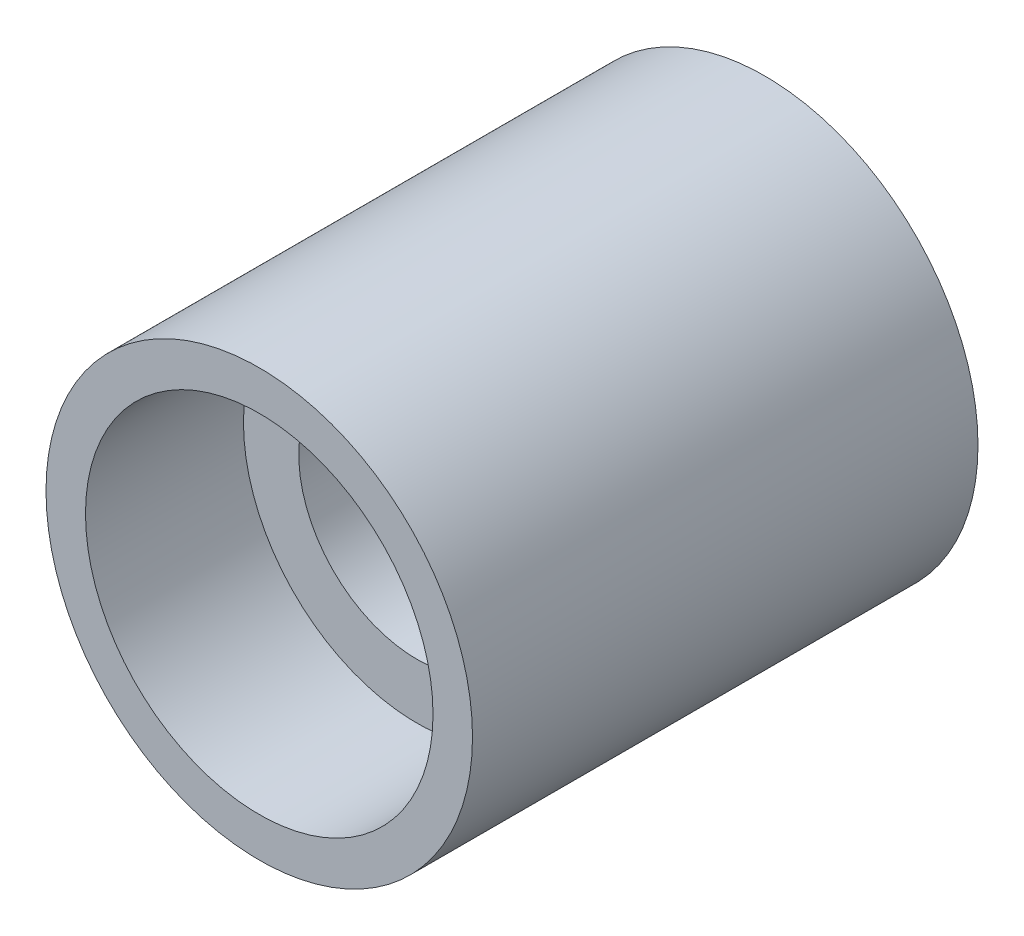
SolidWorks part; units mm, degrees
ref_plane "Front Plane" through (0, 0, 0) normal (0, 0, 1) x (1, 0, 0)
ref_plane "Top Plane" through (0, 0, 0) normal (0, 1, 0) x (1, 0, 0)
ref_plane "Right Plane" through (0, 0, 0) normal (1, 0, 0) x (0, 0, -1)
sketch "Sketch2" plane through (0, 0, 0) normal (0, 0, 1) x (1, 0, 0)
  circle A0 centre (0, 0) radius 13.5
  dimension "D1" = 27
extrude "Boss-Extrude1" add sketch "Sketch2" against normal blind 32
ref_plane "Plane1" through (0, 0, 0) normal (0, 0, 1) x (1, 0, 0)
sketch "Sketch4" plane through (0, 0, 0) normal (0, 0, 1) x (1, 0, 0)
  circle A0 centre (0, 0) radius 11
  dimension "D1" = 22
extrude "Cut-Extrude1" cut sketch "Sketch4" against normal blind 10
sketch "Sketch5" plane through (0, 0, 0) normal (0, 0, 1) x (1, 0, 0)
  circle A0 centre (0, 0) radius 7.5
  dimension "D1" = 15
extrude "Cut-Extrude2" cut sketch "Sketch5" against normal blind 30
